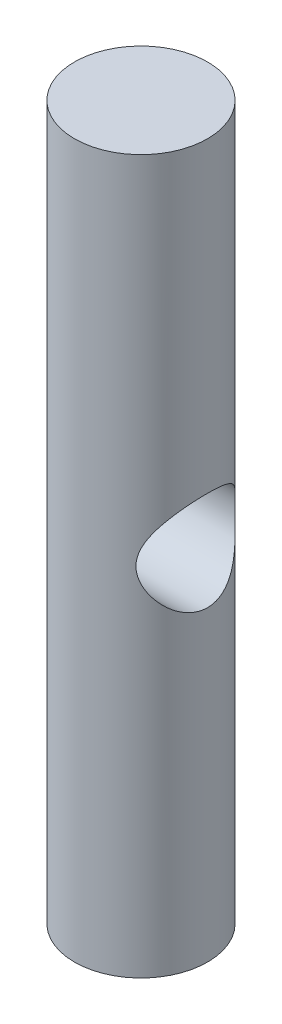
SolidWorks part; units mm, degrees
ref_plane "Front Plane" through (0, 0, 0) normal (0, 0, 1) x (1, 0, 0)
ref_plane "Top Plane" through (0, 0, 0) normal (0, 1, 0) x (1, 0, 0)
ref_plane "Right Plane" through (0, 0, 0) normal (1, 0, 0) x (0, 0, -1)
sketch "Sketch1" plane through (0, 0, 0) normal (0, 1, 0) x (1, 0, 0)
  circle A0 centre (0, 0) radius 10.668
  dimension "D1" = 21.336
extrude "Boss-Extrude1" add sketch "Sketch1" along normal blind 114.3
sketch "Sketch2" plane through (0, 0, 0) normal (1, 0, 0) x (0, 0, -1)
  line L0 (10.668, 0) -> (10.668, 114.3) construction
  circle A0 centre (0, 57.15) radius 7.9375
  dimension "D3" = 15.875
  dimension "D1" = 57.15
  dimension "D2" = 10.668
extrude "Cut-Extrude1" cut sketch "Sketch2" along normal through all both and the other way through all contours A0
